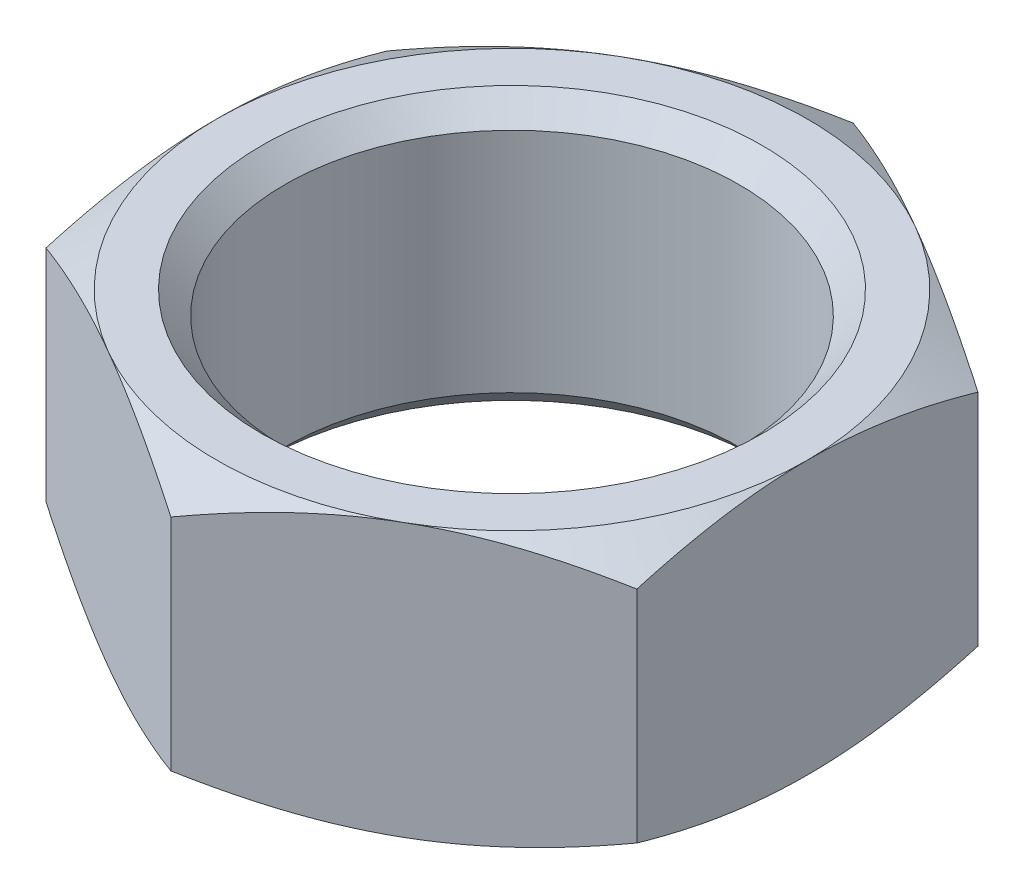
SolidWorks part; units mm, degrees
ref_plane "Front Plane" through (0, 0, 0) normal (0, 0, 1) x (1, 0, 0)
ref_plane "Top Plane" through (0, 0, 0) normal (0, 1, 0) x (1, 0, 0)
ref_plane "Right Plane" through (0, 0, 0) normal (1, 0, 0) x (0, 0, -1)
sketch "Sketch1" plane through (0, 0, 0) normal (0, 1, 0) x (1, 0, 0)
  line L1 (13, 7.5056) -> (0, 15.0111)
  line L2 (0, 15.0111) -> (-13, 7.5056)
  line L3 (-13, 7.5056) -> (-13, -7.5056)
  line L4 (-13, -7.5056) -> (0, -15.0111)
  line L5 (0, -15.0111) -> (13, -7.5056)
  line L6 (13, -7.5056) -> (13, 7.5056)
  circle A0 centre (0, 0) radius 13 construction
  dimension "D1" = 26
extrude "Boss-Extrude1" add sketch "Sketch1" along normal mid plane 12
sketch "Sketch2" plane through (0, 6, 0) normal (0, 1, 0) x (1, 0, 0)
  line L0 (0, 15.0111) -> (-13, 7.5056) construction
  circle A0 centre (0, 0) radius 13
extrude "Cut-Extrude1" cut sketch "Sketch2" against normal blind 12 draft 60 flip side to cut
mirror "Mirror1" about plane through (0, 0, 0) normal (0, 1, 0) of "Cut-Extrude1"
sketch "Sketch3" plane through (0, 6, 0) normal (0, 1, 0) x (1, 0, 0)
  circle A0 centre (0, 0) radius 10
  dimension "D1" = 20
extrude "Cut-Extrude2" cut sketch "Sketch3" against normal through all
chamfer "Chamfer1" distance 1 angle 45 2 edges at (0, -6, 10) (0, 6, 10)
